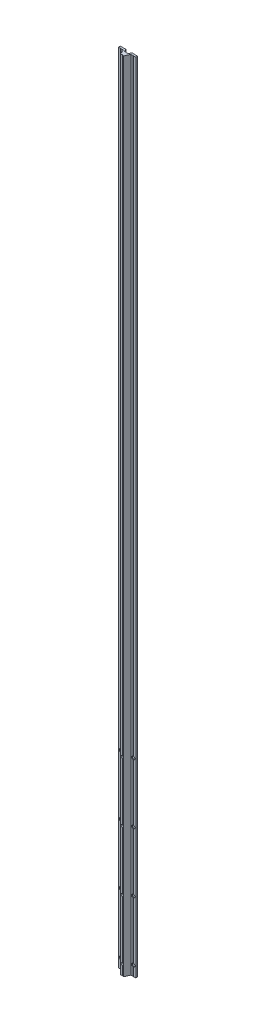
SolidWorks part; units mm, degrees
ref_plane "Plano frontal" through (0, 0, 0) normal (0, 0, 1) x (1, 0, 0)
ref_plane "Plano superior" through (0, 0, 0) normal (0, 1, 0) x (1, 0, 0)
ref_plane "Plano direito" through (0, 0, 0) normal (1, 0, 0) x (0, 0, -1)
ref_plane "Plano1" through (0, 0, 0) normal (0, -1, 0) x (1, 0, 0)
sketch "Esboço1" plane through (0, 0, 0) normal (0, -1, 0) x (1, 0, 0)
  line L0 (-21.925, -26.8) -> (21.925, -26.8)
  line L1 (21.925, -26.8) -> (21.925, -22.1)
  line L2 (21.925, -22.1) -> (9.425, -22.1)
  line L3 (9.425, -22.1) -> (3.8, -9.2499)
  line L4 (3.8, -9.2499) -> (0, -10.811)
  line L5 (0, -10.811) -> (-3.8, -9.2499)
  line L6 (-3.8, -9.2499) -> (-9.425, -22.1)
  line L7 (-9.425, -22.1) -> (-21.925, -22.1)
  line L8 (-21.925, -22.1) -> (-21.925, -26.8)
extrude "Ressalto-extrusão1" add sketch "Esboço1" against normal blind 2000
sketch "Esboço2" plane through (0, 2000, 0) normal (0, 1, 0) x (-1, 0, 0)
  line L0 (-7.925, -26.8) -> (7.925, -26.8)
  line L1 (7.925, -26.8) -> (4.5, -20.3)
  line L2 (4.5, -20.3) -> (0.5, -20.3)
  line L3 (0.5, -20.3) -> (0, -19.8)
  line L4 (0, -19.8) -> (-0.5, -20.3)
  line L5 (-0.5, -20.3) -> (-4.5, -20.3)
  line L6 (-4.5, -20.3) -> (-7.925, -26.8)
extrude "Corte-extrusão1" cut sketch "Esboço2" against normal through all
sketch "Esboço3" plane through (0, 2000, 0) normal (0, 1, 0) x (-1, 0, 0)
  line L0 (-15.175, -26.8) -> (-15.675, -26.3)
  line L1 (-15.675, -26.3) -> (-16.175, -26.8)
  line L2 (-16.175, -26.8) -> (-15.175, -26.8)
extrude "Corte-extrusão2" cut sketch "Esboço3" against normal through all
sketch "Esboço4" plane through (0, 2000, 0) normal (0, 1, 0) x (-1, 0, 0)
  line L0 (-15.175, -22.1) -> (-16.175, -22.1)
  line L1 (-16.175, -22.1) -> (-15.675, -22.6)
  line L2 (-15.675, -22.6) -> (-15.175, -22.1)
extrude "Corte-extrusão3" cut sketch "Esboço4" against normal through all
sketch "Esboço5" plane through (0, 2000, 0) normal (0, 1, 0) x (-1, 0, 0)
  line L0 (16.175, -22.1) -> (15.175, -22.1)
  line L1 (15.175, -22.1) -> (15.675, -22.6)
  line L2 (15.675, -22.6) -> (16.175, -22.1)
extrude "Corte-extrusão4" cut sketch "Esboço5" against normal through all
sketch "Esboço6" plane through (0, 2000, 0) normal (0, 1, 0) x (-1, 0, 0)
  line L0 (15.175, -26.8) -> (16.175, -26.8)
  line L1 (16.175, -26.8) -> (15.675, -26.3)
  line L2 (15.675, -26.3) -> (15.175, -26.8)
extrude "Corte-extrusão5" cut sketch "Esboço6" against normal through all
ref_plane "Plano2" through (0, 325, 0) normal (0, -1, 0) x (1, 0, 0)
sketch "Esboço7" plane through (0, 325, 0) normal (0, -1, 0) x (1, 0, 0)
  line L0 (19.775, -22.1) -> (15.675, -22.1)
  line L1 (15.675, -22.1) -> (15.675, -26.8)
  line L2 (15.675, -26.8) -> (18.81, -26.8)
  line L3 (18.81, -26.8) -> (18.81, -23.065)
  line L4 (18.81, -23.065) -> (19.775, -22.1)
  line L5 (15.675, -22.1) -> (15.675, -26.8) construction
revolve "Corte-Revolução1" cut sketch "Esboço7" angle 360 about L5
ref_plane "Plano3" through (0, 475, 0) normal (0, -1, 0) x (1, 0, 0)
sketch "Esboço8" plane through (0, 475, 0) normal (0, -1, 0) x (1, 0, 0)
  line L0 (19.775, -22.1) -> (15.675, -22.1)
  line L1 (15.675, -22.1) -> (15.675, -26.8)
  line L2 (15.675, -26.8) -> (18.81, -26.8)
  line L3 (18.81, -26.8) -> (18.81, -23.065)
  line L4 (18.81, -23.065) -> (19.775, -22.1)
  line L5 (15.675, -22.1) -> (15.675, -26.8) construction
revolve "Corte-Revolução2" cut sketch "Esboço8" angle 360 about L5
ref_plane "Plano4" through (0, 25, 0) normal (0, -1, 0) x (1, 0, 0)
sketch "Esboço9" plane through (0, 25, 0) normal (0, -1, 0) x (1, 0, 0)
  line L0 (19.775, -22.1) -> (15.675, -22.1)
  line L1 (15.675, -22.1) -> (15.675, -26.8)
  line L2 (15.675, -26.8) -> (18.81, -26.8)
  line L3 (18.81, -26.8) -> (18.81, -23.065)
  line L4 (18.81, -23.065) -> (19.775, -22.1)
  line L5 (15.675, -22.1) -> (15.675, -26.8) construction
revolve "Corte-Revolução3" cut sketch "Esboço9" angle 360 about L5
ref_plane "Plano5" through (0, 175, 0) normal (0, -1, 0) x (1, 0, 0)
sketch "Esboço10" plane through (0, 175, 0) normal (0, -1, 0) x (1, 0, 0)
  line L0 (19.775, -22.1) -> (15.675, -22.1)
  line L1 (15.675, -22.1) -> (15.675, -26.8)
  line L2 (15.675, -26.8) -> (18.81, -26.8)
  line L3 (18.81, -26.8) -> (18.81, -23.065)
  line L4 (18.81, -23.065) -> (19.775, -22.1)
  line L5 (15.675, -22.1) -> (15.675, -26.8) construction
revolve "Corte-Revolução4" cut sketch "Esboço10" angle 360 about L5
sketch "Esboço11" plane through (0, 175, 0) normal (0, -1, 0) x (1, 0, 0)
  line L0 (-11.575, -22.1) -> (-15.675, -22.1)
  line L1 (-15.675, -22.1) -> (-15.675, -26.8)
  line L2 (-15.675, -26.8) -> (-12.54, -26.8)
  line L3 (-12.54, -26.8) -> (-12.54, -23.065)
  line L4 (-12.54, -23.065) -> (-11.575, -22.1)
  line L5 (-15.675, -22.1) -> (-15.675, -26.8) construction
revolve "Corte-Revolução5" cut sketch "Esboço11" angle 360 about L5
sketch "Esboço12" plane through (0, 325, 0) normal (0, -1, 0) x (1, 0, 0)
  line L0 (-11.575, -22.1) -> (-15.675, -22.1)
  line L1 (-15.675, -22.1) -> (-15.675, -26.8)
  line L2 (-15.675, -26.8) -> (-12.54, -26.8)
  line L3 (-12.54, -26.8) -> (-12.54, -23.065)
  line L4 (-12.54, -23.065) -> (-11.575, -22.1)
  line L5 (-15.675, -22.1) -> (-15.675, -26.8) construction
revolve "Corte-Revolução6" cut sketch "Esboço12" angle 360 about L5
sketch "Esboço13" plane through (0, 475, 0) normal (0, -1, 0) x (1, 0, 0)
  line L0 (-11.575, -22.1) -> (-15.675, -22.1)
  line L1 (-15.675, -22.1) -> (-15.675, -26.8)
  line L2 (-15.675, -26.8) -> (-12.54, -26.8)
  line L3 (-12.54, -26.8) -> (-12.54, -23.065)
  line L4 (-12.54, -23.065) -> (-11.575, -22.1)
  line L5 (-15.675, -22.1) -> (-15.675, -26.8) construction
revolve "Corte-Revolução7" cut sketch "Esboço13" angle 360 about L5
sketch "Esboço14" plane through (0, 25, 0) normal (0, -1, 0) x (1, 0, 0)
  line L0 (-11.575, -22.1) -> (-15.675, -22.1)
  line L1 (-15.675, -22.1) -> (-15.675, -26.8)
  line L2 (-15.675, -26.8) -> (-12.54, -26.8)
  line L3 (-12.54, -26.8) -> (-12.54, -23.065)
  line L4 (-12.54, -23.065) -> (-11.575, -22.1)
  line L5 (-15.675, -22.1) -> (-15.675, -26.8) construction
revolve "Corte-Revolução8" cut sketch "Esboço14" angle 360 about L5
ref_plane "Plano6" through (0, 0, -9.5231) normal (0, 0, 1) x (1, 0, 0)
hole_wizard "Furo1" positions "Esboço16" profile "Esboço15" legacy
sketch "Esboço16" plane through (0, 0, -9.5231) normal (0, 0, 1) x (1, 0, 0)
  point P0 (0, 175)
  point P1 (0, 25)
  point P2 (0, 475)
  point P3 (0, 325)
sketch "Esboço15" plane through (0, 175, -9.5231) normal (1, 0, 0) x (0, -1, 0)
  line L0 (0, 0) -> (0, 17.2769)
  line L1 (0, 17.2769) -> (3.135, 17.2769)
  line L2 (3.135, 17.2769) -> (3.135, 0)
  line L3 (3.135, 0) -> (0, 0)
  line L4 (0, 110) -> (0, -10) construction
  dimension "Diameter" = 6.27
  dimension "Depth" = 17.2769
